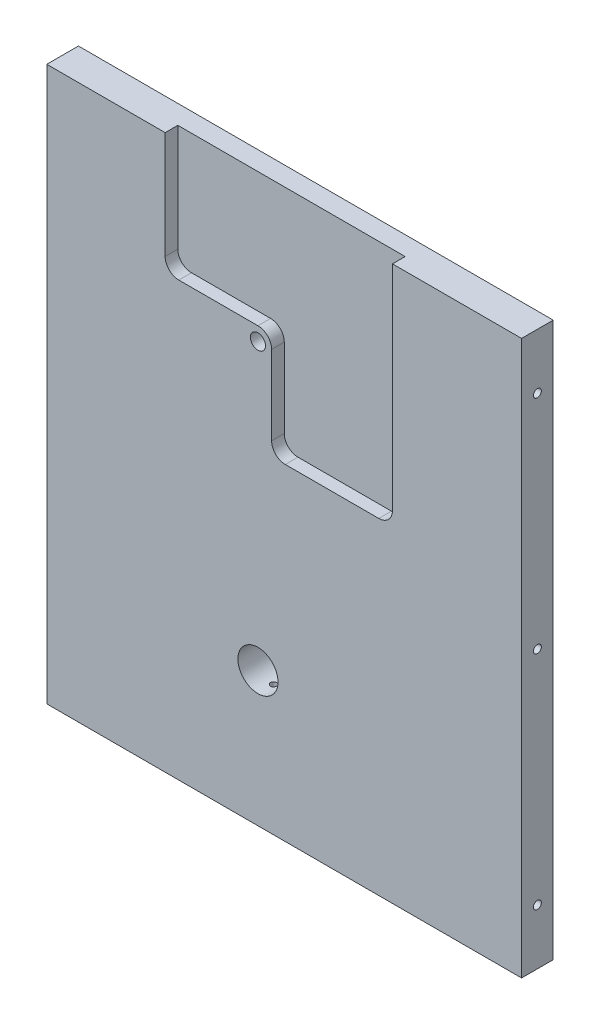
SolidWorks part; units mm, degrees
material "AISI 1020"
ref_plane "Ebene vorne" through (0, 0, 0) normal (0, 0, 1) x (1, 0, 0)
ref_plane "Ebene oben" through (0, 0, 0) normal (0, 1, 0) x (1, 0, 0)
ref_plane "Ebene rechts" through (0, 0, 0) normal (1, 0, 0) x (0, 0, -1)
sketch "Skizze1" plane through (0, 0, 0) normal (0, 0, 1) x (1, 0, 0)
  line L1 (-96.1409, 69.4002) -> (53.8591, 69.4002)
  line L2 (-96.1409, 69.4002) -> (-96.1409, -105.5998)
  line L3 (-96.1409, -105.5998) -> (53.8591, -105.5998)
  line L4 (53.8591, 69.4002) -> (53.8591, -105.5998)
  dimension "D1" = 150
  dimension "D2" = 175
extrude "Aufsatz-Linear austragen1" add sketch "Skizze1" along normal blind 10
sketch "Skizze2" plane through (0, 0, 10) normal (0, 0, 1) x (1, 0, 0)
  line L0 (-96.1409, -18.0998) -> (53.8591, -18.0998) construction
  line L1 (-96.1409, 69.4002) -> (-96.1409, -105.5998) construction
  line L2 (-96.1409, -18.0998) -> (33.5831, 69.4002) construction
  line L3 (53.8591, 69.4002) -> (-96.1409, 69.4002) construction
  line L4 (-96.1409, -18.0998) -> (33.5831, -105.5998) construction
  line L5 (-96.1409, -105.5998) -> (53.8591, -105.5998) construction
  line L6 (-29.4257, 26.9002) -> (53.8591, 26.9002) construction
  line L11 (53.8591, -105.5998) -> (53.8591, 69.4002) construction
  line L12 (-29.4257, -63.0998) -> (-29.4257, 26.9002) construction
  line L13 (53.8591, -8.0998) -> (-96.1409, -8.0998) construction
  line L14 (53.8591, -28.0998) -> (-96.1409, -28.0998) construction
  line L15 (-21.1409, -28.0998) -> (-21.1409, -8.0998) construction
  circle A0 centre (-29.4257, 26.9002) radius 2.3876
  circle A1 centre (-29.4257, -63.0998) radius 6.335
  point P29 (-21.1409, -18.0998)
  dimension "D4" = 4.7752
  dimension "D6" = 12.67
  dimension "D1" = 34
  dimension "D2" = 34
  dimension "D3" = 90
  dimension "D10" = 20
extrude "Schnitt-Linear austragen1" cut sketch "Skizze2" against normal blind 10
sketch "Skizze3" plane through (0, 0, 10) normal (0, 0, 1) x (1, 0, 0)
  line L1 (-54.4257, 31.2182) -> (-54.4257, 69.4002) construction
  line L7 (-54.4257, 31.2182) -> (-29.4257, 31.2182)
  line L8 (-25.1077, 26.9002) -> (-25.1077, 1.9002)
  line L9 (-20.7897, -2.4178) -> (8.7563, -2.4178)
  line L10 (13.0743, 1.9002) -> (13.0743, 69.4002)
  line L11 (53.8591, 69.4002) -> (-96.1409, 69.4002) construction
  line L12 (-58.7437, 35.5362) -> (-58.7437, 69.4002)
  line L13 (-58.7437, 69.4002) -> (13.0743, 69.4002)
  line L14 (-25.1077, 1.9002) -> (13.0743, 1.9002) construction
  arc A3 (-29.4257, 31.2182) -> (-25.1077, 26.9002) centre (-29.4257, 26.9002) cw
  arc A4 (-25.1077, 1.9002) -> (-20.7897, -2.4178) centre (-20.7897, 1.9002) ccw
  arc A5 (8.7563, -2.4178) -> (13.0743, 1.9002) centre (8.7563, 1.9002) ccw
  arc A6 (-54.4257, 31.2182) -> (-58.7437, 35.5362) centre (-54.4257, 35.5362) cw
  circle A7 centre (-29.4257, 26.9002) radius 2.3876 construction
  dimension "D1" = 4.318
  dimension "D2" = 25
  dimension "D3" = 25
extrude "Schnitt-Linear austragen2" cut sketch "Skizze3" against normal blind 4
sketch "Skizze4" plane through (-96.1409, 0, 0) normal (-1, 0, 0) x (0, 0, 1)
  line L0 (0, -18.0998) -> (10, -18.0998) construction
  line L1 (5, -88.0998) -> (5, -18.0998) construction
  line L2 (5, -18.0998) -> (5, 51.9002) construction
  line L4 (10, 69.4002) -> (10, -105.5998) construction
  line L5 (0, 69.4002) -> (0, -105.5998) construction
  circle A0 centre (5, 51.9002) radius 1.25
  circle A1 centre (5, -18.0998) radius 1.25
  circle A3 centre (5, -88.0998) radius 1.25
  point P7 (5, -18.0998)
  dimension "D2" = 2.5
  dimension "D1" = 70
extrude "Schnitt-Linear austragen3" cut sketch "Skizze4" against normal blind 5
sketch "Skizze6" plane through (53.8591, 0, 0) normal (1, 0, 0) x (0, 0, -1)
  line L0 (-10, -18.0998) -> (0, -18.0998) construction
  line L1 (-5, -88.0998) -> (-5, -18.0998) construction
  line L2 (-5, -18.0998) -> (-5, 51.9002) construction
  line L4 (0, -105.5998) -> (0, 69.4002) construction
  line L5 (-10, -105.5998) -> (-10, 69.4002) construction
  circle A0 centre (-5, 51.9002) radius 1.25
  circle A1 centre (-5, -18.0998) radius 1.25
  circle A3 centre (-5, -88.0998) radius 1.25
  point P7 (-5, -18.0998)
  dimension "D2" = 2.5
  dimension "D1" = 70
extrude "Schnitt-Linear austragen4" cut sketch "Skizze6" against normal blind 5
sketch "Skizze7" plane through (0, -105.5998, 0) normal (0, -1, 0) x (1, 0, 0)
  line L0 (-29.4209, 0) -> (-29.4209, 10) construction
  line L1 (-96.1409, 0) -> (53.8591, 0) construction
  line L2 (-96.1409, 10) -> (53.8591, 10) construction
  line L3 (-96.1409, 10) -> (-96.1409, 0) construction
  circle A0 centre (-29.4209, 5) radius 1
  dimension "D1" = 2
  dimension "D2" = 66.72
extrude "Schnitt-Linear austragen5" cut sketch "Skizze7" against normal blind 40
